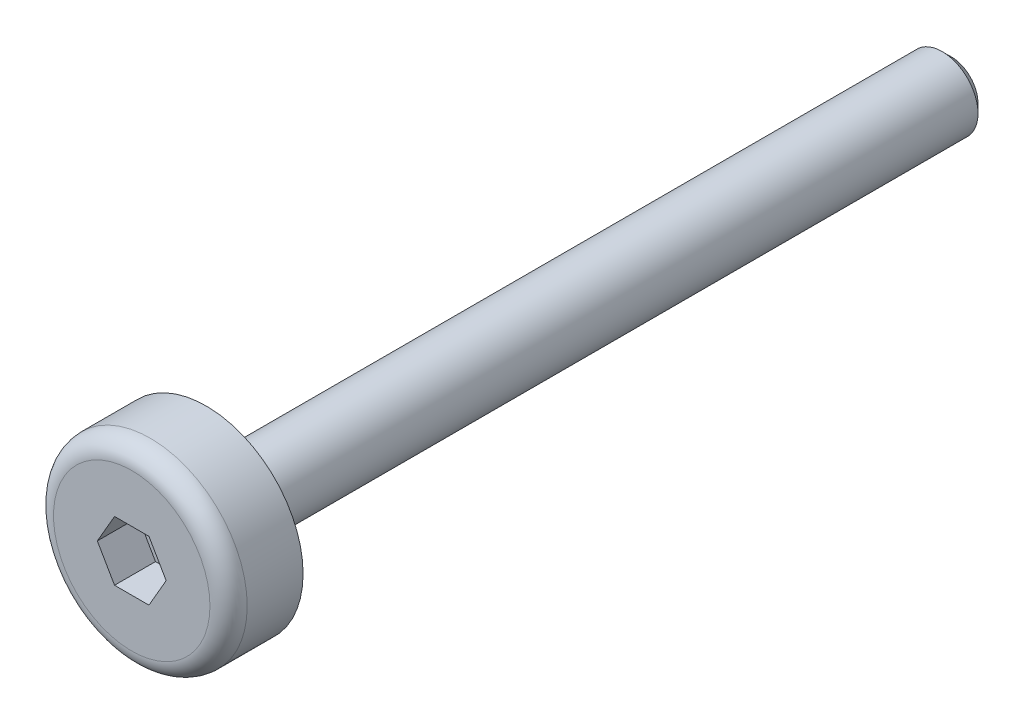
SolidWorks part; units mm, degrees
ref_plane "Front Plane" through (0, 0, 0) normal (0, 0, 1) x (1, 0, 0)
ref_plane "Top Plane" through (0, 0, 0) normal (0, 1, 0) x (1, 0, 0)
ref_plane "Right Plane" through (0, 0, 0) normal (1, 0, 0) x (0, 0, -1)
sketch "Screw Section" plane through (0, 0, 0) normal (0, 1, 0) x (1, 0, 0)
  line L0 (0, 25) -> (1.2, 25)
  line L1 (1.2, 25) -> (1.2, 0)
  line L2 (1.2, 0) -> (3.25, 0)
  line L3 (3.25, 0) -> (3.25, -2.5)
  line L4 (3.25, -2.5) -> (0, -2.5)
  line L5 (0, -2.5) -> (0, 25)
  line L6 (0, -10.123) -> (0, 10.123) construction
  dimension "D1" = 1.2
  dimension "D2" = 3.25
  dimension "D3" = 25
  dimension "D4" = 2.5
  dimension "D5" = 10.123
  dimension "D6" = 10.123
revolve "Screw Blank Revolve" add sketch "Screw Section" angle 360 about L6
chamfer "Shank Tip Chamfer" distance 0.3 1 edges at (1.2, 0, -25)
fillet "Pan Head Round" radius 0.625 1 edges at (3.25, 0, 2.5)
ref_plane "Head Crown Plane" through (0, 0, 2.5) normal (0, 0, 1) x (1, 0, 0)
sketch "Hex Drive Sketch" plane through (0, 0, 2.5) normal (0, 0, 1) x (1, 0, 0)
  line L1 (1.1547, 0) -> (0.5774, 1)
  line L2 (0.5774, 1) -> (-0.5774, 1)
  line L3 (-0.5774, 1) -> (-1.1547, 0)
  line L4 (-1.1547, 0) -> (-0.5774, -1)
  line L5 (-0.5774, -1) -> (0.5774, -1)
  line L6 (0.5774, -1) -> (1.1547, 0)
  circle A0 centre (0, 0) radius 1 construction
  dimension "D1" = 2
extrude "Hex Drive Cut" cut sketch "Hex Drive Sketch" against normal blind 1.375
equation "\"nominal_length\"= 25.0mm 'Screw length: under pan head or including flat head"
equation "\"model_shank_radius\"= 1.2mm 'Clearance envelope minor shank radius; thread is not modeled"
equation "\"head_diameter\"= 6.5mm 'Head outside diameter"
equation "\"head_height\"= 2.5mm 'Head axial height"
equation "\"drive_across_flats\"= 2mm 'Hex drive across flats"
equation "\"tip_chamfer\"= 0.3mm 'Shank tip chamfer"
equation "\"head_round\"= 0.625mm 'Pan head crown edge radius"
equation "\"drive_depth\"= 1.375mm 'Hex socket depth"
equation "\"axis_reference_halfspan\"= 10.123mm 'Half display length of the construction axis; avoids sharing a profile endpoint"
equation "\"D1@Screw Section\"= \"model_shank_radius\""
equation "\"D2@Screw Section\"= \"head_diameter\" / 2"
equation "\"D3@Screw Section\"= \"nominal_length\""
equation "\"D4@Screw Section\"= \"head_height\""
equation "\"D5@Screw Section\"= \"axis_reference_halfspan\""
equation "\"D6@Screw Section\"= \"axis_reference_halfspan\""
equation "\"full_turn\"= 360deg 'Full circular extent for revolves and patterns"
equation "\"D1@Screw Blank Revolve\"= \"full_turn\""
equation "\"D1@Shank Tip Chamfer\"= \"tip_chamfer\""
equation "\"D1@Pan Head Round\"= \"head_round\""
equation "\"D1@Head Crown Plane\"= \"head_height\""
equation "\"D1@Hex Drive Sketch\"= \"drive_across_flats\""
equation "\"D1@Hex Drive Cut\"= \"drive_depth\""
